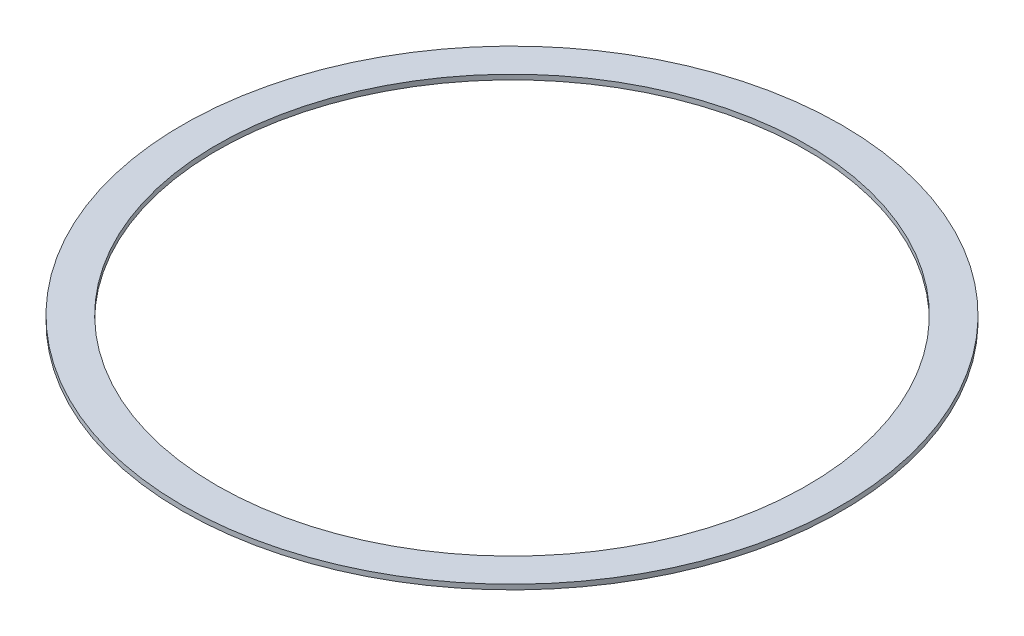
SolidWorks part; units mm, degrees
material "AISI 304"
ref_plane "Piano frontale" through (0, 0, 0) normal (0, 0, 1) x (1, 0, 0)
ref_plane "Piano superiore" through (0, 0, 0) normal (0, 1, 0) x (1, 0, 0)
ref_plane "Piano destro" through (0, 0, 0) normal (1, 0, 0) x (0, 0, -1)
sketch "Schizzo1" plane through (0, 0, 0) normal (0, 1, 0) x (1, 0, 0)
  circle A0 centre (0, 0) radius 67
  circle A1 centre (0, 0) radius 60
extrude "Estrusione-Estrusione1" add sketch "Schizzo1" along normal mid plane 1
